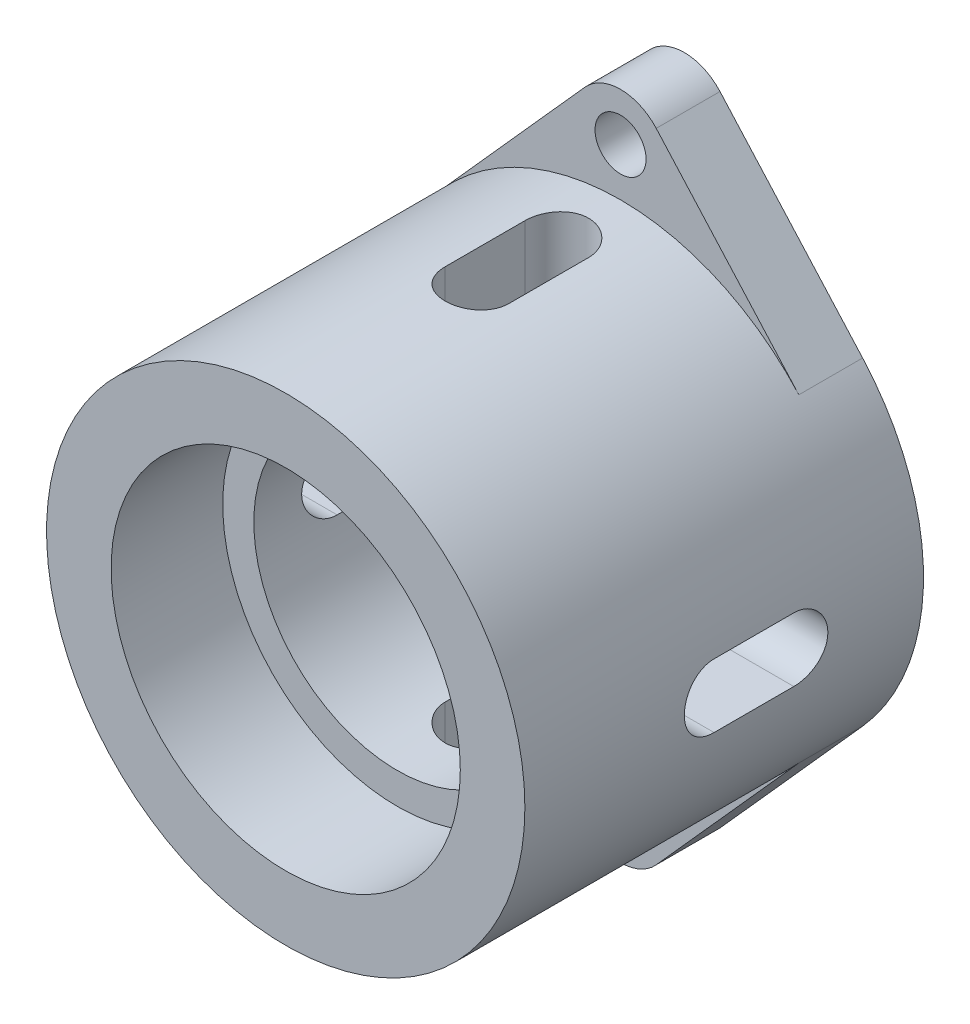
SolidWorks part; units mm, degrees
ref_plane "Alzado" through (0, 0, 0) normal (1, 0, 0) x (0, 1, 0)
ref_plane "Planta" through (0, 0, 0) normal (0, 0, 1) x (0, 1, 0)
ref_plane "Vista lateral" through (0, 0, 0) normal (0, 1, 0) x (-1, 0, 0)
sketch "Croquis1" plane through (0, 0, 0) normal (0, 0, 1) x (0, 1, 0)
  circle A0 centre (0, 0) radius 9
  circle A1 centre (0, 0) radius 11 construction
  circle A2 centre (0, 0) radius 15
  dimension "D1" = 18
  dimension "D2" = 22
  dimension "D3" = 4
extrude "Saliente-Extruir1" add sketch "Croquis1" along normal blind 25
sketch "Croquis2" plane through (0, 0, 25) normal (0, 0, 1) x (1, 0, 0)
  circle A0 centre (0, 0) radius 10.95
  dimension "D1" = 21.9
extrude "Cortar-Extruir1" cut sketch "Croquis2" against normal blind 7
sketch "Croquis3" plane through (0, 0, 0) normal (0, 0, 1) x (0, 1, 0)
  line L0 (-9.9997, -11.1806) -> (-20.0002, -2.2364)
  line L1 (-20.0002, 2.2364) -> (-9.9997, 11.1806)
  line L2 (-18, 0) -> (0, 0) construction
  circle A0 centre (0, 0) radius 15 construction
  circle A2 centre (-18, 0) radius 1.6
  circle A3 centre (-18, 0) radius 3.0004
  circle A4 centre (0, 0) radius 15
  point P1 (-15, 0)
  point P11 (-15, 0)
  dimension "D2" = 30
  dimension "D3" = 3.2
  dimension "D4" = 6.0008
  dimension "D1" = 18
extrude "Saliente-Extruir2" add sketch "Croquis3" along normal blind 4
mirror "Simetría1" about plane through (0, 0, 0) normal (0, 1, 0) of "Saliente-Extruir2"
sketch "Croquis4" plane through (0, 0, 0) normal (1, 0, 0) x (0, 1, 0)
  line L0 (0, 8) -> (0, 13) construction
  line L1 (-2, 8) -> (-2, 13)
  line L2 (2, 8) -> (2, 13)
  line L3 (-9.9997, 4) -> (-20.0002, 4) construction
  arc A0 (-2, 8) -> (2, 8) centre (0, 8) ccw
  arc A1 (2, 13) -> (-2, 13) centre (0, 13) ccw
  point P3 (0, 10.5)
  dimension "D1" = 5
  dimension "D2" = 4
  dimension "D3" = 4
extrude "Cortar-Extruir2" cut sketch "Croquis4" against normal blind 26
pattern_circular "MatrizC1" count 4 over 360 about axis through (0, 0, 0) along (0, 0, 1) of "Cortar-Extruir2"
